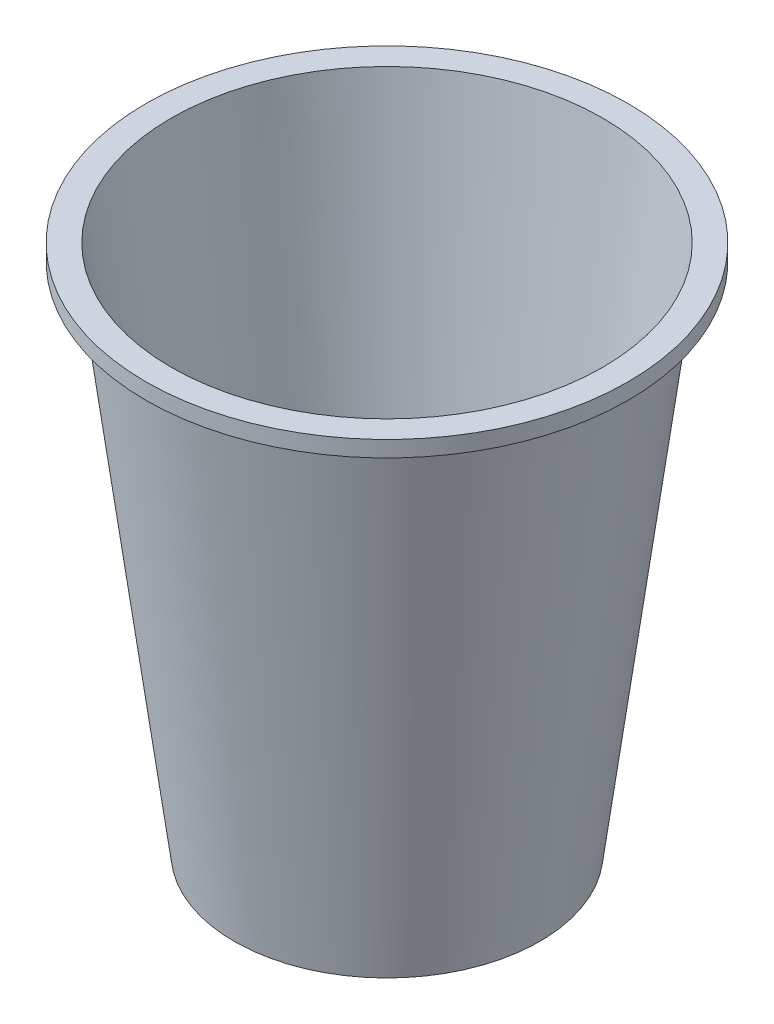
SolidWorks part; units mm, degrees
ref_plane "Plan de face" through (0, 0, 0) normal (0, 0, 1) x (1, 0, 0)
ref_plane "Plan de dessus" through (0, 0, 0) normal (0, 1, 0) x (1, 0, 0)
ref_plane "Plan de droite" through (0, 0, 0) normal (1, 0, 0) x (0, 0, -1)
sketch "Esquisse1" plane through (0, 0, 0) normal (0, 0, 1) x (1, 0, 0)
  line L0 (0, 0) -> (31.5, 0)
  line L1 (31.5, 0) -> (45.5, 109)
  line L2 (45.5, 109) -> (0, 109)
  line L3 (0, 109) -> (0, 0)
  dimension "D1" = 31.5
  dimension "D2" = 45.5
  dimension "D3" = 109
revolve "Révolution1" add sketch "Esquisse1" angle 360 about L3
shell "Coque1" thickness 1
sketch "Esquisse2" plane through (0, 109, 0) normal (0, 1, 0) x (1, 0, 0)
  circle A4 centre (0, 0) radius 49.69
  circle A5 centre (0, 0) radius 44.4918
  circle A7 centre (0, 0) radius 44.4918 construction
  dimension "D1" = 99.38
extrude "Boss.-Extru.1" add sketch "Esquisse2" against normal blind 3.3
